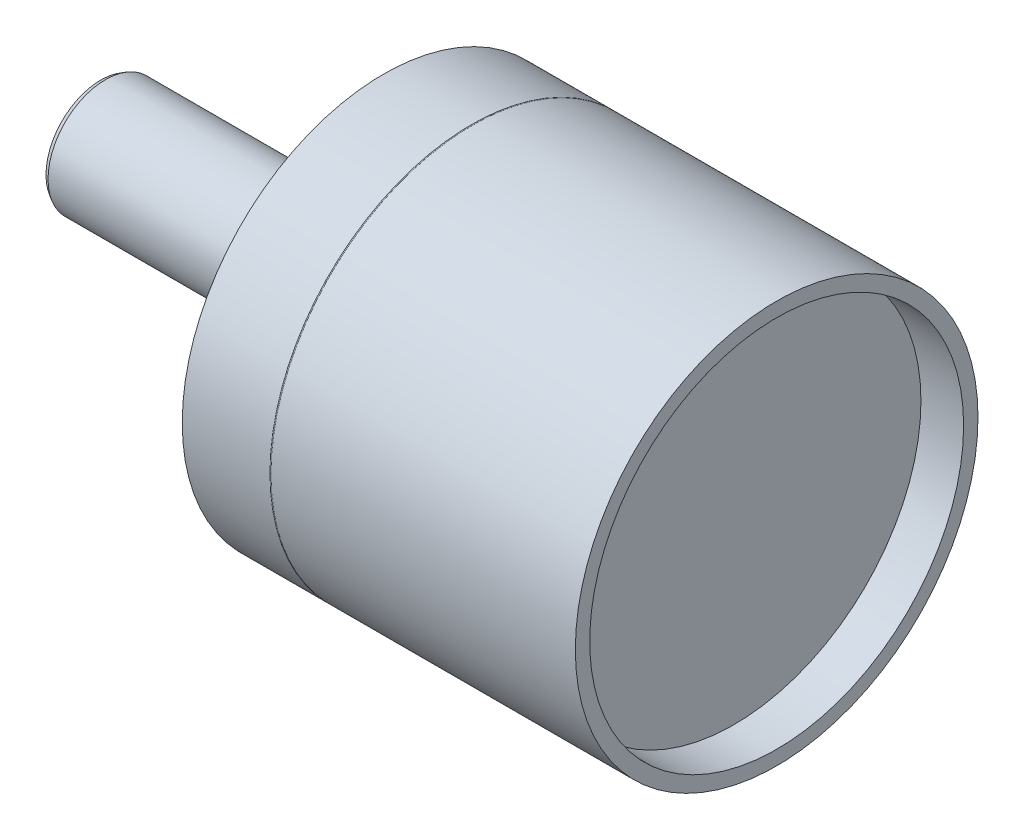
SolidWorks part; units mm, degrees
ref_plane "Front Plane" through (0, 0, 0) normal (0, 0, 1) x (1, 0, 0)
ref_plane "Top Plane" through (0, 0, 0) normal (0, 1, 0) x (1, 0, 0)
ref_plane "Right Plane" through (0, 0, 0) normal (1, 0, 0) x (0, 0, -1)
sketch "Sketch1" plane through (0, 0, 0) normal (0, 0, 1) x (1, 0, 0)
  line L0 (0, 21) -> (0, 0)
  line L1 (0, 0) -> (41, 0)
  line L2 (41, 0) -> (41, 21)
  line L3 (41, 21) -> (9.25, 21)
  line L4 (9.15, 21) -> (0, 21)
  line L5 (0, 0) -> (41, 0) construction
  arc A0 (9.25, 21) -> (9.15, 21) centre (9.2, 21.0866) cw
revolve "Revolve1" add sketch "Sketch1" angle 360 about L5
sketch "Sketch2" plane through (0, 0, 0) normal (-1, 0, 0) x (0, 0, 1)
  circle A0 centre (0, 0) radius 14
extrude "Boss-Extrude1" add sketch "Sketch2" along normal blind 3
sketch "Sketch3" plane through (-3, 0, 0) normal (-1, 0, 0) x (0, 0, 1)
  circle A0 centre (0, 0) radius 6
extrude "Boss-Extrude2" add sketch "Sketch3" along normal blind 26.5
sketch "Sketch4" plane through (-3, 0, 0) normal (-1, 0, 0) x (0, 0, 1)
  line L0 (0.2939, -7.6168) -> (0.2939, -5.9928)
  line L1 (-0.2939, -5.9928) -> (-0.2939, -7.6168)
  arc A0 (0.2939, -5.9928) -> (-0.2939, -5.9928) centre (0, 0) ccw
  arc A1 (-0.2939, -7.6168) -> (-2.8825, -5.9928) centre (0.2939, -3.8048) cw
  arc A2 (-2.8825, -5.9928) -> (2.8825, -5.9928) centre (0, 0) cw
  arc A3 (2.8825, -5.9928) -> (0.2939, -7.6168) centre (0.2939, -4.7418) cw
extrude "Boss-Extrude3" add sketch "Sketch4" along normal blind 1
hole_wizard "M36 Clearance Hole1" positions "Sketch7" profile "Sketch6" hole size "M36" standard "ANSI Metric"
sketch "Sketch7" plane through (41, 0, 0) normal (1, 0, 0) x (0, 0, -1)
  point P0 (0, 0)
sketch "Sketch6" plane through (41, 0, 0) normal (0, 1, 0) x (0, 0, -1)
  line L0 (0, 0) -> (0, 4.45)
  line L1 (0, 4.45) -> (19.5, 4.45)
  line L2 (19.5, 4.45) -> (19.5, 0)
  line L5 (19.5, 0) -> (0, 0)
  line L10 (0, 4.45) -> (-19.5, 4.45) construction
  line L11 (0, -6.35) -> (0, 107.95) construction
  dimension "Hole Dia." = 39
  dimension "Hole Depth" = 4.45
  dimension "Drill Angle" = 180
hole_wizard "Ø1.5 (1.5) Diameter Hole1" positions "Sketch9" profile "Sketch8" hole size "Ø1.5" standard "ANSI Metric"
sketch "Sketch9" plane through (0, 0, 0) normal (-1, 0, 0) x (0, 0, 1)
  point P0 (-7.4623, 18.0157)
sketch "Sketch8" plane through (0, 18.0157, -7.4623) normal (0, 1, 0) x (0, 0, 1)
  line L0 (0, 0) -> (0, 2.4506)
  line L1 (0, 2.4506) -> (0.75, 2)
  line L2 (0.75, 2) -> (0.75, 0)
  line L5 (0.75, 0) -> (0, 0)
  line L10 (0, 2.4506) -> (-0.75, 2) construction
  line L11 (0, -6.35) -> (0, 107.95) construction
  dimension "Hole Dia." = 1.5
  dimension "Hole Depth" = 2
  dimension "Drill Angle" = 118
hole_wizard "Ø3.3 (3.3) Diameter Hole1" positions "Sketch11" profile "Sketch10" hole size "Ø3.3" standard "ANSI Metric"
sketch "Sketch11" plane through (0, 0, 0) normal (-1, 0, 0) x (0, 0, 1)
  point P0 (0, 17.5)
  point P1 (17.5, 0)
  point P2 (0, -17.5)
  point P3 (-17.5, 0)
sketch "Sketch10" plane through (0, 17.5, 0) normal (0, 1, 0) x (0, 0, 1)
  line L0 (0, 0) -> (0, 6.9914)
  line L1 (0, 6.9914) -> (1.65, 6)
  line L2 (1.65, 6) -> (1.65, 0)
  line L5 (1.65, 0) -> (0, 0)
  line L10 (0, 6.9914) -> (-1.65, 6) construction
  line L11 (0, -6.35) -> (0, 107.95) construction
  dimension "Hole Dia." = 3.3
  dimension "Hole Depth" = 6
  dimension "Drill Angle" = 118
hole_wizard "Ø1.25 (1.25) Diameter Hole1" positions "Sketch13" profile "Sketch12" hole size "Ø1.25" standard "ANSI Metric"
sketch "Sketch13" plane through (-29.5, 0, 0) normal (-1, 0, 0) x (0, 0, 1)
  point P0 (0, 0)
sketch "Sketch12" plane through (-29.5, 0, 0) normal (0, 1, 0) x (0, 0, 1)
  line L0 (0, 0) -> (0, 2.3)
  line L1 (0, 2.3) -> (0.625, 1.9392)
  line L2 (0.625, 1.9392) -> (0.625, 1.2124)
  line L3 (0.625, 1.2124) -> (1.325, 0)
  line L5 (1.325, 0) -> (0, 0)
  line L6 (-0.625, 1.2124) -> (-1.325, 0) construction
  line L10 (0, 2.3) -> (-0.625, 1.9392) construction
  line L11 (0, -6.35) -> (0, 107.95) construction
  dimension "Hole Dia." = 1.25
  dimension "Hole Depth" = 1.9392
  dimension "Near C'Sink Dia." = 2.65
  dimension "Near C'Sink Angle" = 60
  dimension "Drill Angle" = 120
chamfer "Chamfer1" distance 0.2887 angle 60 1 edges at (-29.5, 0, 6)
